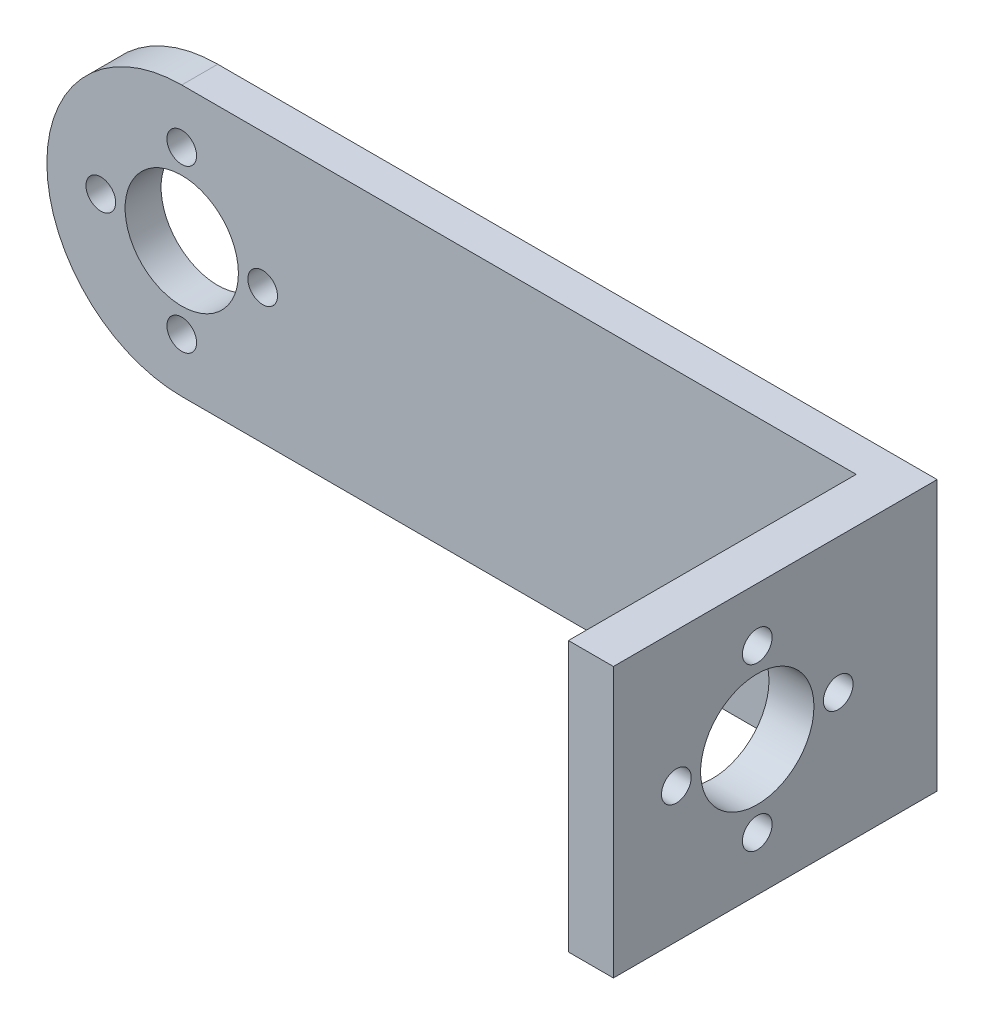
SolidWorks part; units mm, degrees
ref_plane "前视基准面" through (0, 0, 0) normal (0, 0, 1) x (1, 0, 0)
ref_plane "上视基准面" through (0, 0, 0) normal (0, 1, 0) x (1, 0, 0)
ref_plane "右视基准面" through (0, 0, 0) normal (1, 0, 0) x (0, 0, -1)
sketch "草图1" plane through (0, 0, 0) normal (0, 0, 1) x (1, 0, 0)
  line L0 (0, 15) -> (0, -15)
  line L1 (0, 15) -> (80, 15)
  line L2 (0, -15) -> (80, -15)
  line L3 (80, 15) -> (80, -15)
  circle A0 centre (0, 0) radius 9
  circle A1 centre (0, 0) radius 6.3
  circle A2 centre (-9, 0) radius 1.65
  circle A3 centre (0, 9) radius 1.65
  circle A4 centre (9, 0) radius 1.65
  circle A5 centre (0, -9) radius 1.65
  circle A6 centre (0, 0) radius 15
extrude "凸台-拉伸1" add sketch "草图1" along normal blind 4 contours L0 A6 A5 A0 A2 A3 | A5 L0 A1 A3 A0 A2 | A5 A0 A4 A3 L0 A1 | L0 A6 A3 A0 A4 A5 | A6 L2 L3 L1
sketch "草图2" plane through (0, 0, 0) normal (0, 0, 1) x (1, 0, 0)
  line L0 (80, 15) -> (80, -15)
  line L1 (80, 15) -> (75, 15)
  line L2 (80, -15) -> (75, -15)
  line L3 (75, 15) -> (75, -15)
extrude "凸台-拉伸2" add sketch "草图2" along normal blind 36
sketch "草图4" plane through (80, 0, 0) normal (1, 0, 0) x (0, 0, -1)
  line L0 (-36, 15) -> (-36, -15)
  line L1 (-36, 15) -> (-4, 15)
  line L2 (-36, -15) -> (-4, -15)
  line L3 (-4, 15) -> (-4, -15)
  line L4 (-20, 15) -> (-20, -15)
  circle A0 centre (-20, 0) radius 9
  circle A1 centre (-20, 0) radius 6.3
  circle A2 centre (-29, 0) radius 1.65
  circle A3 centre (-20, 9) radius 1.65
  circle A4 centre (-11, 0) radius 1.65
  circle A5 centre (-20, -9) radius 1.65
extrude "切除-拉伸1" cut sketch "草图4" against normal blind 34 contours L4 A3 A0 | A0 A3 L4 | A0 A3 L4 | L4 A3 A0 | L4 A1 | L4 A1 | A0 A2 | A0 A2 | L4 A5 A0 | A0 A5 L4 | L4 A5 A0 | A0 A5 L4 | A0 A4 | A0 A4
